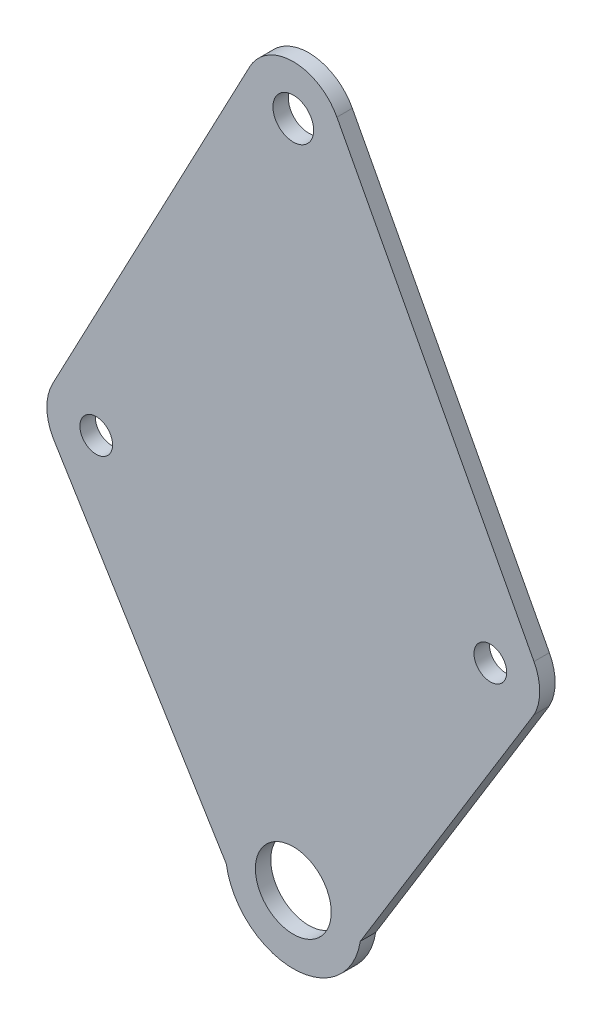
SolidWorks part; units mm, degrees
material "6061-T6 (SS)"
ref_plane "X-Y Datum" through (0, 0, 0) normal (0, 0, 1) x (1, 0, 0)
ref_plane "X-Z Datum" through (0, 0, 0) normal (0, 1, 0) x (1, 0, 0)
ref_plane "Y-Z Datum" through (0, 0, 0) normal (1, 0, 0) x (0, 0, -1)
sketch "Sketch1" plane through (0, 0, 0) normal (0, 0, 1) x (1, 0, 0)
  line L0 (0, 0) -> (0, 137.668) construction
  line L1 (0, 137.668) -> (40.5829, 60.8625) construction
  line L2 (40.5829, 60.8625) -> (0, 0) construction
  line L3 (-13.97, 0) -> (-10.16, 137.668)
  line L4 (8.9831, 142.4145) -> (49.566, 65.6091)
  line L5 (49.566, 56.116) -> (8.1778, -11.3263)
  line L6 (-40.5829, 60.8625) -> (0, 0) construction
  line L7 (0, 137.668) -> (-40.5829, 60.8625) construction
  line L8 (-49.566, 56.116) -> (-8.1778, -11.3263)
  line L9 (-8.9831, 142.4145) -> (-49.566, 65.6091)
  line L10 (13.97, 0) -> (10.16, 137.668)
  circle A0 centre (0, 0) radius 7.8105
  circle A1 centre (40.5829, 60.8625) radius 3.3655
  circle A2 centre (0, 137.668) radius 4.191
  arc A3 (-10.16, 137.668) -> (8.9831, 142.4145) centre (0, 137.668) cw
  arc A4 (49.566, 65.6091) -> (49.566, 56.116) centre (40.5829, 60.8625) cw
  arc A5 (8.1778, -11.3263) -> (-13.97, 0) centre (0, 0) cw
  arc A6 (-10.16, 137.668) -> (-13.97, 0) centre (-120.8325, 71.8442) cw
  circle A7 centre (0, 0) radius 11.5718
  circle A8 centre (-40.5829, 60.8625) radius 3.3655
  arc A9 (-8.1778, -11.3263) -> (13.97, 0) centre (0, 0) ccw
  arc A10 (-49.566, 65.6091) -> (-49.566, 56.116) centre (-40.5829, 60.8625) ccw
  arc A11 (10.16, 137.668) -> (-8.9831, 142.4145) centre (0, 137.668) ccw
  point P16 (50.7429, 60.8625)
  dimension "D4" = 15.621
  dimension "D5" = 6.731
  dimension "D6" = 8.382
  dimension "D7" = 13.97
  dimension "D8" = 10.16
  dimension "D9" = 10.16
  dimension "D10" = 23.1436
  dimension "D12" = 128.7679
  dimension "D1" = 137.668
  dimension "D2" = 86.868
  dimension "D3" = 73.152
  dimension "D11" = 125.83
extrude "Boss-Extrude1" add sketch "Sketch1" along normal blind 3.175 contours L9 A10 L8 A5 L3 A3 A8 | A11 L10 A9 L5 A4 L4 A1 | L10 A11 A3 A6 A5 L8 L5 A9 A2 A7 | A6 L3 | L5 A9 | A5 L8 | A7 A0
